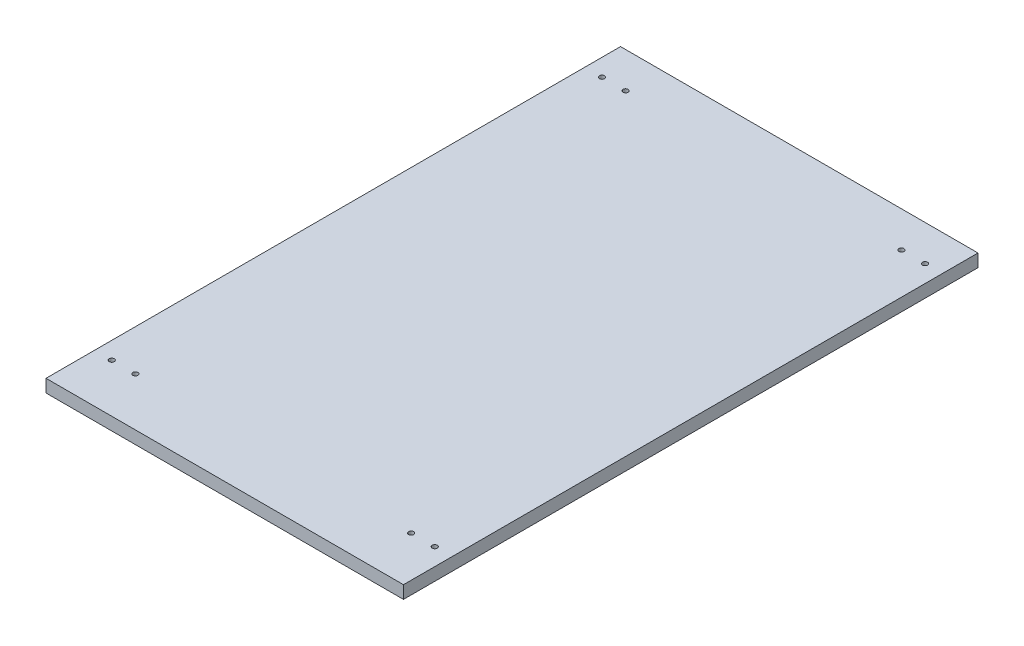
SolidWorks part; units mm, degrees
material "Pino"
ref_plane "Piano frontale" through (0, 0, 0) normal (0, 0, 1) x (1, 0, 0)
ref_plane "Piano superiore" through (0, 0, 0) normal (0, 1, 0) x (1, 0, 0)
ref_plane "Piano destro" through (0, 0, 0) normal (1, 0, 0) x (0, 0, -1)
sketch "Schizzo1" plane through (0, 0, 0) normal (0, 1, 0) x (1, 0, 0)
  line L1 (0, 0) -> (-280, 0)
  line L2 (0, 0) -> (0, 450)
  line L3 (0, 450) -> (-280, 450)
  line L4 (-280, 0) -> (-280, 450)
  dimension "D1" = 280
  dimension "D2" = 450
extrude "Estrusione-Estrusione1" add sketch "Schizzo1" along normal blind 10
sketch "Schizzo2" plane through (0, 10, 0) normal (0, 1, 0) x (1, 0, 0)
  circle A0 centre (-266.5, 38) radius 2
  circle A1 centre (-248, 38) radius 2
  circle A2 centre (-32, 38) radius 2
  circle A3 centre (-13.5, 38) radius 2
  circle A4 centre (-13.5, 422) radius 2
  circle A5 centre (-32, 422) radius 2
  circle A6 centre (-266.5, 422) radius 2
  circle A7 centre (-248, 422) radius 2
  dimension "D5" = 4
extrude "Taglio-Estrusione1" cut sketch "Schizzo2" against normal blind 10
